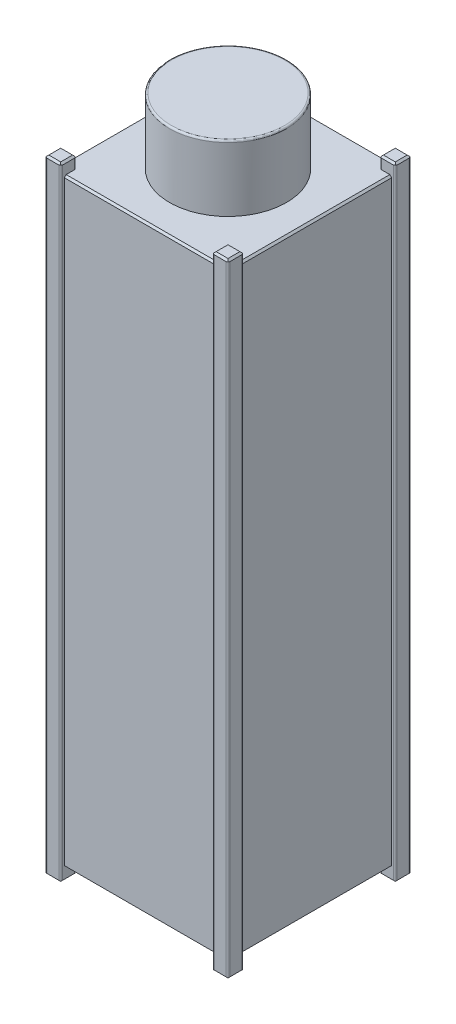
SolidWorks part; units mm, degrees
material "ABS"
ref_plane "Front Plane" through (0, 0, 0) normal (0, 0, 1) x (1, 0, 0)
ref_plane "Top Plane" through (0, 0, 0) normal (0, 1, 0) x (1, 0, 0)
ref_plane "Right Plane" through (0, 0, 0) normal (1, 0, 0) x (0, 0, -1)
sketch "Sketch1" plane through (0, 0, 0) normal (0, 1, 0) x (1, 0, 0)
  line L1 (-50, -50) -> (50, -50)
  line L2 (-50, -50) -> (-50, 50)
  line L3 (-50, 50) -> (50, 50)
  line L4 (50, -50) -> (50, 50)
  dimension "D1" = 50
  dimension "D2" = 50
  dimension "D3" = 50
  dimension "D4" = 50
extrude "Boss-Extrude1" add sketch "Sketch1" along normal blind 327.8
sketch "Sketch2" plane through (0, 327.8, 0) normal (0, 1, 0) x (1, 0, 0)
  line L0 (0, 50) -> (0, -50) construction
  line L1 (-50, 50) -> (50, 50) construction
  line L2 (-50, 50) -> (-50, -50) construction
  line L3 (-50, -50) -> (50, -50) construction
  line L4 (50, 50) -> (50, -50) construction
  line L5 (-50, 0) -> (50, 0) construction
  line L6 (41.5, 50) -> (41.5, 41.5)
  line L7 (-50, 50) -> (-41.5, 50)
  line L8 (-50, 50) -> (-50, 41.5)
  line L9 (-50, 41.5) -> (-41.5, 41.5)
  line L10 (-41.5, 50) -> (-41.5, 41.5)
  line L11 (50, 50) -> (41.5, 50)
  line L12 (50, 50) -> (50, 41.5)
  line L13 (50, 41.5) -> (41.5, 41.5)
  line L14 (50, -41.5) -> (41.5, -41.5)
  line L15 (50, -50) -> (50, -41.5)
  line L16 (50, -50) -> (41.5, -50)
  line L17 (-41.5, -50) -> (-41.5, -41.5)
  line L18 (-50, -41.5) -> (-41.5, -41.5)
  line L19 (-50, -50) -> (-50, -41.5)
  line L20 (-50, -50) -> (-41.5, -50)
  line L21 (41.5, -50) -> (41.5, -41.5)
  dimension "D1" = 8.5
  dimension "D2" = 8.5
extrude "Boss-Extrude2" add sketch "Sketch2" along normal blind 6.5
chamfer "Chamfer1" distance 1 angle 45 16 edges at (45.75, 334.3, -41.5) (41.5, 334.3, -45.75) (45.75, 334.3, -50) (50, 334.3, -45.75) (41.5, 334.3, 45.75) (45.75, 334.3, 41.5) (50, 334.3, 45.75) (45.75, 334.3, 50) (-50, 334.3, 45.75) (-45.75, 334.3, 41.5) (-41.5, 334.3, 45.75) (-45.75, 334.3, 50) (-45.75, 334.3, -50) (-41.5, 334.3, -45.75) (-45.75, 334.3, -41.5) (-50, 334.3, -45.75)
sketch "Sketch3" plane through (0, 327.8, 0) normal (0, 1, 0) x (1, 0, 0)
  circle A0 centre (0, 0) radius 32
  dimension "D1" = 64
extrude "Boss-Extrude3" add sketch "Sketch3" along normal blind 36
sketch "Sketch5" plane through (0, 0, 0) normal (0, 0, 1) x (1, 0, 0)
  line L0 (0, 327.8) -> (0, 0) construction
  line L1 (-41.5, 327.8) -> (41.5, 327.8) construction
  line L2 (-50, 163.9) -> (50, 163.9) construction
  line L3 (-50, 333.3) -> (-50, 0) construction
  line L4 (50, 333.3) -> (50, 0) construction
ref_plane "Plane1" through (0, 163.9, 0) normal (0, 1, 0) x (1, 0, 0)
mirror "Mirror1" about plane through (0, 163.9, 0) normal (0, 1, 0) of "Chamfer1", "Boss-Extrude2"
fillet "Fillet1" radius 1 4 edges at (50, 163.9, -50) (50, 163.9, 50) (-50, 163.9, 50) (-50, 163.9, -50)
sketch "Sketch6" plane through (0, 0, -50) normal (0, 0, -1) x (-1, 0, 0)
  line L1 (-41.5, 327.8) -> (41.5, 327.8)
  line L2 (-41.5, 327.8) -> (-41.5, 0)
  line L3 (-41.5, 0) -> (41.5, 0)
  line L4 (41.5, 327.8) -> (41.5, 0)
extrude "Cut-Extrude1" cut sketch "Sketch6" against normal blind 2
pattern_circular "CirPattern1" count 4 over 360 about axis through (0, 0, 0) along (0, 1, 0) of "Cut-Extrude1"
fillet "Fillet2" radius 1 1 edges at (0, 363.8, 32)
fillet "Fillet3" radius 1 18 edges at (41.5, -2.75, -41.5) (41.5, -2.75, 41.5) (-41.5, -2.75, 41.5) (-41.5, -2.75, -41.5) (50, 163.9, -41.5) (41.5, 330.55, -41.5) (41.5, 163.9, -50) (50, 163.9, 41.5) (41.5, 163.9, 50) (41.5, 330.55, 41.5) (-41.5, 163.9, 50) (-50, 163.9, 41.5) (-41.5, 330.55, 41.5) (-41.5, 330.55, -41.5)
chamfer "Chamfer2" distance 1 angle 45 8 edges at (48, 0, 0) (0, 0, 48) (0, 0, -48) (-48, 0, 0) (48, 327.8, 0) (0, 327.8, -48) (0, 327.8, 48) (-48, 327.8, 0)
ref_plane "2UCube" through (0, 220.7, 0) normal (0, -1, 0) x (-1, 0, 0)
ref_plane "1UCube" through (0, 107, 0) normal (0, -1, 0) x (-1, 0, 0)
sketch "1UCubeRef" plane through (0, 107, 0) normal (0, -1, 0) x (-1, 0, 0)
  line L1 (-49, 49) -> (49, 49) construction
  line L2 (-49, 49) -> (-49, -49) construction
  line L3 (-49, -49) -> (49, -49) construction
  line L4 (49, 49) -> (49, -49) construction
sketch "2UCubeRef" plane through (0, 220.7, 0) normal (0, -1, 0) x (-1, 0, 0)
  line L1 (49, 49) -> (-49, 49) construction
  line L2 (49, 49) -> (49, -49) construction
  line L3 (49, -49) -> (-49, -49) construction
  line L4 (-49, 49) -> (-49, -49) construction
sketch "Sketch10" plane through (0, 363.8, 0) normal (0, 1, 0) x (1, 0, 0)
  circle A0 centre (0, 0) radius 76.2 construction
  dimension "D1" = 152.4
